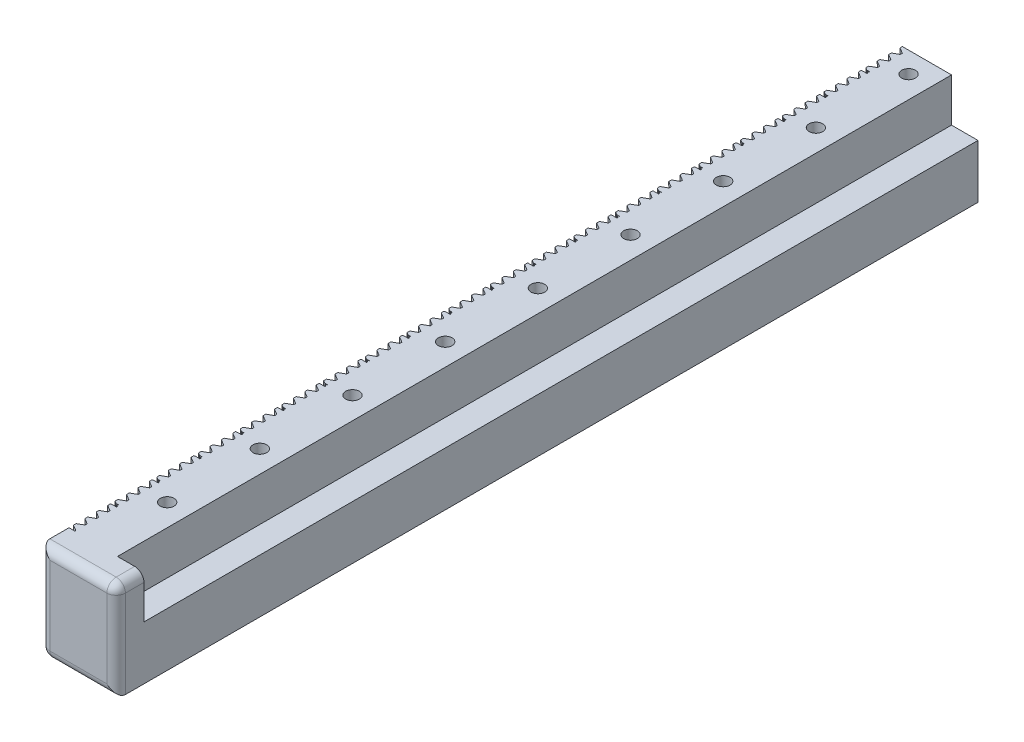
SolidWorks part; units mm, degrees
ref_plane "Front Plane" through (0, 0, 0) normal (0, 0, 1) x (1, 0, 0)
ref_plane "Top Plane" through (0, 0, 0) normal (0, 1, 0) x (1, 0, 0)
ref_plane "Right Plane" through (0, 0, 0) normal (1, 0, 0) x (0, 0, -1)
sketch "Sketch1" plane through (0, 0, 0) normal (0, 0, 1) x (1, 0, 0)
  line L0 (8.155, 3.5595) -> (8.155, -2.2289)
  line L1 (6.255, 0) -> (0.2882, 0)
  line L3 (0, 8.253) -> (5.3, 8.253)
  line L4 (5.3, 3.5595) -> (5.3, 8.253)
  line L5 (0.2882, 0) -> (0, 8.253)
  line L7 (5.3, 3.5595) -> (8.155, 3.5595)
  line L11 (8.155, -2.2289) -> (6.255, -2.2289)
  line L12 (6.255, 0) -> (6.255, -2.2289)
  dimension "D1" = 5.3
  dimension "D2" = 8.253
  dimension "D3" = 1.9
  dimension "D4" = 2.855
  dimension "D6" = 88
extrude "Boss-Extrude1" add sketch "Sketch1" along normal blind 90
sketch "Sketch2" plane through (0, 0, 90) normal (0, 0, 1) x (1, 0, 0)
  line L1 (0, 8.253) -> (8.155, 8.253)
  line L2 (0, 8.253) -> (0, -2.2289)
  line L3 (0, -2.2289) -> (8.155, -2.2289)
  line L4 (8.155, 8.253) -> (8.155, -2.2289)
extrude "Boss-Extrude2" add sketch "Sketch2" along normal blind 3
fillet "Fillet1" radius 1 6 edges at (4.0775, 8.253, 93) (8.155, 3.0121, 93) (4.0775, -2.2289, 93) (0, 3.0121, 93) (0, -2.2289, 91.5) (8.155, 8.253, 91.5)
sketch "Sketch3" plane through (5.3, 0, 0) normal (0, 1, 0) x (0, 0, -1)
  line L0 (-87.5812, 4.6774) -> (-88.0715, 5.5507)
  line L1 (-88.0715, 5.5507) -> (-88.5898, 4.6774)
  line L2 (-88.8112, 4.6774) -> (-89.3015, 5.5507)
  line L3 (-89.3015, 5.5507) -> (-89.8198, 4.6774)
  line L4 (-89.3983, 4.4813) -> (-88.7803, 4.4739) [skipped]
  line L5 (-86.3512, 4.6774) -> (-86.8415, 5.5507)
  line L6 (-86.8415, 5.5507) -> (-87.3598, 4.6774)
  line L7 (-85.1212, 4.6774) -> (-85.6115, 5.5507)
  line L8 (-85.6115, 5.5507) -> (-86.1298, 4.6774)
  line L149 (-89.9324, 4.6774) -> (-89.9324, 6.9221)
  line L150 (-89.9324, 6.9221) -> (-85.1212, 6.9221)
  line L154 (-89.8198, 4.6774) -> (-89.9324, 4.6774)
  line L155 (-88.5898, 4.6774) -> (-88.8112, 4.6774)
  line L156 (-87.3598, 4.6774) -> (-87.5812, 4.6774)
  line L157 (-86.1298, 4.6774) -> (-86.3512, 4.6774)
  line L158 (-85.1212, 6.9221) -> (-85.1212, 4.6774)
  line L160 (-83.1621, 7.6054) -> (-83.4775, 7.0739) [skipped]
  line L161 (-83.735, 6.5902) -> (-84.3402, 7.668) [skipped]
  line L162 (-81.9321, 7.6054) -> (-82.5629, 6.5424) [skipped]
  line L163 (-82.505, 6.5902) -> (-83.1102, 7.668) [skipped]
  line L164 (-80.7021, 7.6054) -> (-81.3329, 6.5424) [skipped]
  line L165 (-81.275, 6.5902) -> (-81.8802, 7.668) [skipped]
  line L166 (-79.4721, 7.6054) -> (-80.1029, 6.5424) [skipped]
  line L167 (-80.045, 6.5902) -> (-80.6502, 7.668) [skipped]
  line L168 (-78.2421, 7.6054) -> (-78.8729, 6.5424) [skipped]
  line L169 (-78.815, 6.5902) -> (-79.4202, 7.668) [skipped]
  line L170 (-77.0121, 7.6054) -> (-77.6429, 6.5424) [skipped]
  line L171 (-75.7821, 7.6054) -> (-76.4129, 6.5424) [skipped]
  line L172 (-84.965, 6.5902) -> (-85.5702, 7.668) [skipped]
  line L173 (-49.295, 6.5902) -> (-49.9002, 7.668) [skipped]
  line L174 (-47.4921, 7.6054) -> (-48.1229, 6.5424) [skipped]
  line L175 (-48.065, 6.5902) -> (-48.6702, 7.668) [skipped]
  line L176 (-46.2621, 7.6054) -> (-46.8929, 6.5424) [skipped]
  line L177 (-46.835, 6.5902) -> (-47.4402, 7.668) [skipped]
  line L178 (-45.0321, 7.6054) -> (-45.6629, 6.5424) [skipped]
  line L179 (-45.605, 6.5902) -> (-46.2102, 7.668) [skipped]
  line L180 (-43.8021, 7.6054) -> (-44.4329, 6.5424) [skipped]
  line L181 (-44.375, 6.5902) -> (-44.9802, 7.668) [skipped]
  line L182 (-42.5721, 7.6054) -> (-43.2029, 6.5424) [skipped]
  line L183 (-43.145, 6.5902) -> (-43.7502, 7.668) [skipped]
  line L184 (-41.3421, 7.6054) -> (-41.9729, 6.5424) [skipped]
  line L185 (-41.915, 6.5902) -> (-42.5202, 7.668) [skipped]
  line L186 (-40.1121, 7.6054) -> (-40.7429, 6.5424) [skipped]
  line L187 (-40.685, 6.5902) -> (-41.2902, 7.668) [skipped]
  line L188 (-38.8821, 7.6054) -> (-39.5129, 6.5424) [skipped]
  line L189 (-37.6521, 7.6054) -> (-38.2829, 6.5424) [skipped]
  line L190 (-38.225, 6.5902) -> (-38.8302, 7.668) [skipped]
  line L191 (-36.4221, 7.6054) -> (-37.0529, 6.5424) [skipped]
  line L192 (-36.995, 6.5902) -> (-37.6002, 7.668) [skipped]
  line L193 (-35.1921, 7.6054) -> (-35.8229, 6.5424) [skipped]
  line L194 (-35.765, 6.5902) -> (-36.3702, 7.668) [skipped]
  line L195 (-33.9621, 7.6054) -> (-34.5929, 6.5424) [skipped]
  line L196 (-34.535, 6.5902) -> (-35.1402, 7.668) [skipped]
  line L197 (-32.7321, 7.6054) -> (-33.3629, 6.5424) [skipped]
  line L198 (-33.305, 6.5902) -> (-33.9102, 7.668) [skipped]
  line L199 (-31.5021, 7.6054) -> (-32.1329, 6.5424) [skipped]
  line L200 (-32.075, 6.5902) -> (-32.6802, 7.668) [skipped]
  line L201 (-30.2721, 7.6054) -> (-30.9029, 6.5424) [skipped]
  line L202 (-30.845, 6.5902) -> (-31.4502, 7.668) [skipped]
  line L203 (-29.0421, 7.6054) -> (-29.6729, 6.5424) [skipped]
  line L204 (-29.615, 6.5902) -> (-30.2202, 7.668) [skipped]
  line L205 (-27.8121, 7.6054) -> (-28.4429, 6.5424) [skipped]
  line L206 (-28.385, 6.5902) -> (-28.9902, 7.668) [skipped]
  line L207 (-26.5821, 7.6054) -> (-27.2129, 6.5424) [skipped]
  line L208 (-27.155, 6.5902) -> (-27.7602, 7.668) [skipped]
  line L209 (-25.3521, 7.6054) -> (-25.9829, 6.5424) [skipped]
  line L210 (-25.925, 6.5902) -> (-26.5302, 7.668) [skipped]
  line L211 (-24.1221, 7.6054) -> (-24.7529, 6.5424) [skipped]
  line L212 (-24.695, 6.5902) -> (-25.3002, 7.668) [skipped]
  line L213 (-22.8921, 7.6054) -> (-23.5229, 6.5424) [skipped]
  line L214 (-23.465, 6.5902) -> (-24.0702, 7.668) [skipped]
  line L215 (-21.6621, 7.6054) -> (-22.2929, 6.5424) [skipped]
  line L216 (-22.235, 6.5902) -> (-22.8402, 7.668) [skipped]
  line L217 (-20.4321, 7.6054) -> (-21.0629, 6.5424) [skipped]
  line L218 (-21.005, 6.5902) -> (-21.6102, 7.668) [skipped]
  line L219 (-19.2021, 7.6054) -> (-19.8329, 6.5424) [skipped]
  line L220 (-19.775, 6.5902) -> (-20.3802, 7.668) [skipped]
  line L221 (-17.9721, 7.6054) -> (-18.6029, 6.5424) [skipped]
  line L222 (-18.545, 6.5902) -> (-19.1502, 7.668) [skipped]
  line L223 (-16.7421, 7.6054) -> (-17.3729, 6.5424) [skipped]
  line L224 (-17.315, 6.5902) -> (-17.9202, 7.668) [skipped]
  line L225 (-15.5121, 7.6054) -> (-16.1429, 6.5424) [skipped]
  line L226 (-16.085, 6.5902) -> (-16.6902, 7.668) [skipped]
  line L227 (-14.2821, 7.6054) -> (-14.9129, 6.5424) [skipped]
  line L228 (-14.855, 6.5902) -> (-15.4602, 7.668) [skipped]
  line L229 (-13.0521, 7.6054) -> (-13.6829, 6.5424) [skipped]
  line L230 (-13.625, 6.5902) -> (-14.2302, 7.668) [skipped]
  line L231 (-11.8221, 7.6054) -> (-12.4529, 6.5424) [skipped]
  line L232 (-12.395, 6.5902) -> (-13.0002, 7.668) [skipped]
  line L233 (-10.5921, 7.6054) -> (-11.2229, 6.5424) [skipped]
  line L234 (-11.165, 6.5902) -> (-11.7702, 7.668) [skipped]
  line L235 (-9.3621, 7.6054) -> (-9.9929, 6.5424) [skipped]
  line L236 (-9.935, 6.5902) -> (-10.5402, 7.668) [skipped]
  line L237 (-8.1321, 7.6054) -> (-8.7629, 6.5424) [skipped]
  line L238 (-8.705, 6.5902) -> (-9.3102, 7.668) [skipped]
  line L239 (-6.9021, 7.6054) -> (-7.5329, 6.5424) [skipped]
  line L240 (-7.475, 6.5902) -> (-8.0802, 7.668) [skipped]
  line L241 (-5.6721, 7.6054) -> (-6.3029, 6.5424) [skipped]
  line L242 (-6.245, 6.5902) -> (-6.8502, 7.668) [skipped]
  line L243 (-4.4421, 7.6054) -> (-5.0729, 6.5424) [skipped]
  line L244 (-5.015, 6.5902) -> (-5.6202, 7.668) [skipped]
  line L245 (-3.2121, 7.6054) -> (-3.8429, 6.5424) [skipped]
  line L246 (-3.785, 6.5902) -> (-4.3902, 7.668) [skipped]
  line L247 (-1.9821, 7.6054) -> (-2.6129, 6.5424) [skipped]
  line L248 (-2.555, 6.5902) -> (-3.1602, 7.668) [skipped]
  line L249 (-0.7521, 7.6054) -> (-1.3829, 6.5424) [skipped]
  line L250 (-1.325, 6.5902) -> (-1.9302, 7.668) [skipped]
  line L251 (0.4779, 7.6054) -> (-0.1529, 6.5424) [skipped]
  line L252 (-0.095, 6.5902) -> (-0.7002, 7.668) [skipped]
  line L253 (1.7079, 7.6054) -> (1.0771, 6.5424) [skipped]
  line L254 (-39.455, 6.5902) -> (-40.0602, 7.668) [skipped]
  line L255 (-76.355, 6.5902) -> (-76.9602, 7.668) [skipped]
  line L256 (-74.5521, 7.6054) -> (-75.1829, 6.5424) [skipped]
  line L257 (-75.125, 6.5902) -> (-75.7302, 7.668) [skipped]
  line L258 (-73.3221, 7.6054) -> (-73.9529, 6.5424) [skipped]
  line L259 (-73.895, 6.5902) -> (-74.5002, 7.668) [skipped]
  line L260 (-72.0921, 7.6054) -> (-72.7229, 6.5424) [skipped]
  line L261 (-72.665, 6.5902) -> (-73.2702, 7.668) [skipped]
  line L262 (-70.8621, 7.6054) -> (-71.4929, 6.5424) [skipped]
  line L263 (-71.435, 6.5902) -> (-72.0402, 7.668) [skipped]
  line L264 (-69.6321, 7.6054) -> (-70.2629, 6.5424) [skipped]
  line L265 (-70.205, 6.5902) -> (-70.8102, 7.668) [skipped]
  line L266 (-68.4021, 7.6054) -> (-69.0329, 6.5424) [skipped]
  line L267 (-68.975, 6.5902) -> (-69.5802, 7.668) [skipped]
  line L268 (-67.1721, 7.6054) -> (-67.8029, 6.5424) [skipped]
  line L269 (-67.745, 6.5902) -> (-68.3502, 7.668) [skipped]
  line L270 (-65.9421, 7.6054) -> (-66.5729, 6.5424) [skipped]
  line L271 (-66.515, 6.5902) -> (-67.1202, 7.668) [skipped]
  line L272 (-64.7121, 7.6054) -> (-65.3429, 6.5424) [skipped]
  line L273 (-65.285, 6.5902) -> (-65.8902, 7.668) [skipped]
  line L274 (-63.4821, 7.6054) -> (-64.1129, 6.5424) [skipped]
  line L275 (-64.055, 6.5902) -> (-64.6602, 7.668) [skipped]
  line L276 (-62.2521, 7.6054) -> (-62.8829, 6.5424) [skipped]
  line L277 (-62.825, 6.5902) -> (-63.4302, 7.668) [skipped]
  line L278 (-61.0221, 7.6054) -> (-61.6529, 6.5424) [skipped]
  line L279 (-61.595, 6.5902) -> (-62.2002, 7.668) [skipped]
  line L280 (-59.7921, 7.6054) -> (-60.4229, 6.5424) [skipped]
  line L281 (-60.365, 6.5902) -> (-60.9702, 7.668) [skipped]
  line L282 (-58.5621, 7.6054) -> (-59.1929, 6.5424) [skipped]
  line L283 (-59.135, 6.5902) -> (-59.7402, 7.668) [skipped]
  line L284 (-57.3321, 7.6054) -> (-57.9629, 6.5424) [skipped]
  line L285 (-57.905, 6.5902) -> (-58.5102, 7.668) [skipped]
  line L286 (-56.1021, 7.6054) -> (-56.7329, 6.5424) [skipped]
  line L287 (-56.675, 6.5902) -> (-57.2802, 7.668) [skipped]
  line L288 (-54.8721, 7.6054) -> (-55.5029, 6.5424) [skipped]
  line L289 (-55.445, 6.5902) -> (-56.0502, 7.668) [skipped]
  line L290 (-53.6421, 7.6054) -> (-54.2729, 6.5424) [skipped]
  line L291 (-54.215, 6.5902) -> (-54.8202, 7.668) [skipped]
  line L292 (-52.4121, 7.6054) -> (-53.0429, 6.5424) [skipped]
  line L293 (-52.985, 6.5902) -> (-53.5902, 7.668) [skipped]
  line L294 (-51.1821, 7.6054) -> (-51.8129, 6.5424) [skipped]
  line L295 (-51.755, 6.5902) -> (-52.3602, 7.668) [skipped]
  line L296 (-49.9521, 7.6054) -> (-50.5829, 6.5424) [skipped]
  line L297 (-50.525, 6.5902) -> (-51.1302, 7.668) [skipped]
  line L298 (-48.7221, 7.6054) -> (-49.3529, 6.5424) [skipped]
  line L299 (-77.585, 6.5902) -> (-78.1902, 7.668) [skipped]
  circle A0 centre (-89.3101, 4.8371) radius 0.3568 construction
  arc A1 (-87.7689, 5.0118) -> (-88.3869, 5.0193) centre (-88.0801, 4.8371) ccw construction
  arc A2 (-86.5389, 5.0118) -> (-87.1692, 4.6774) centre (-86.8501, 4.8371) ccw construction
  arc A3 (-85.9392, 4.6774) -> (-85.301, 4.6774) centre (-85.6201, 4.8371) ccw construction
  arc A74 (-85.3089, 5.0118) -> (-85.9269, 5.0193) centre (-85.6201, 4.8371) ccw construction
  arc A75 (-84.7112, 4.6816) -> (-84.7116, 4.6824) centre (-84.3901, 4.8371) ccw construction
  circle A76 centre (-83.1601, 4.8371) radius 0.3568 construction
  circle A77 centre (-81.9301, 4.8371) radius 0.3568 construction
  circle A78 centre (-80.7001, 4.8371) radius 0.3568 construction
  circle A79 centre (-79.4701, 4.8371) radius 0.3568 construction
  circle A80 centre (-78.2401, 4.8371) radius 0.3568 construction
  circle A81 centre (-77.0101, 4.8371) radius 0.3568 construction
  circle A82 centre (-48.7201, 4.8371) radius 0.3568 construction
  circle A83 centre (-47.4901, 4.8371) radius 0.3568 construction
  circle A84 centre (-46.2601, 4.8371) radius 0.3568 construction
  circle A85 centre (-45.0301, 4.8371) radius 0.3568 construction
  circle A86 centre (-43.8001, 4.8371) radius 0.3568 construction
  circle A87 centre (-42.5701, 4.8371) radius 0.3568 construction
  circle A88 centre (-41.3401, 4.8371) radius 0.3568 construction
  circle A89 centre (-40.1101, 4.8371) radius 0.3568 construction
  circle A90 centre (-38.8801, 4.8371) radius 0.3568 construction
  circle A91 centre (-37.6501, 4.8371) radius 0.3568 construction
  circle A92 centre (-36.4201, 4.8371) radius 0.3568 construction
  circle A93 centre (-35.1901, 4.8371) radius 0.3568 construction
  circle A94 centre (-33.9601, 4.8371) radius 0.3568 construction
  circle A95 centre (-32.7301, 4.8371) radius 0.3568 construction
  circle A96 centre (-31.5001, 4.8371) radius 0.3568 construction
  circle A97 centre (-30.2701, 4.8371) radius 0.3568 construction
  circle A98 centre (-29.0401, 4.8371) radius 0.3568 construction
  circle A99 centre (-27.8101, 4.8371) radius 0.3568 construction
  circle A100 centre (-26.5801, 4.8371) radius 0.3568 construction
  circle A101 centre (-25.3501, 4.8371) radius 0.3568 construction
  circle A102 centre (-24.1201, 4.8371) radius 0.3568 construction
  circle A103 centre (-22.8901, 4.8371) radius 0.3568 construction
  circle A104 centre (-21.6601, 4.8371) radius 0.3568 construction
  circle A105 centre (-20.4301, 4.8371) radius 0.3568 construction
  circle A106 centre (-19.2001, 4.8371) radius 0.3568 construction
  circle A107 centre (-17.9701, 4.8371) radius 0.3568 construction
  circle A108 centre (-16.7401, 4.8371) radius 0.3568 construction
  circle A109 centre (-15.5101, 4.8371) radius 0.3568 construction
  circle A110 centre (-14.2801, 4.8371) radius 0.3568 construction
  circle A111 centre (-13.0501, 4.8371) radius 0.3568 construction
  circle A112 centre (-11.8201, 4.8371) radius 0.3568 construction
  circle A113 centre (-10.5901, 4.8371) radius 0.3568 construction
  circle A114 centre (-9.3601, 4.8371) radius 0.3568 construction
  circle A115 centre (-8.1301, 4.8371) radius 0.3568 construction
  circle A116 centre (-6.9001, 4.8371) radius 0.3568 construction
  circle A117 centre (-5.6701, 4.8371) radius 0.3568 construction
  circle A118 centre (-4.4401, 4.8371) radius 0.3568 construction
  circle A119 centre (-3.2101, 4.8371) radius 0.3568 construction
  circle A120 centre (-1.9801, 4.8371) radius 0.3568 construction
  circle A121 centre (-0.7501, 4.8371) radius 0.3568 construction
  circle A122 centre (0.4799, 4.8371) radius 0.3568 construction
  circle A123 centre (-75.7801, 4.8371) radius 0.3568 construction
  circle A124 centre (-74.5501, 4.8371) radius 0.3568 construction
  circle A125 centre (-73.3201, 4.8371) radius 0.3568 construction
  circle A126 centre (-72.0901, 4.8371) radius 0.3568 construction
  circle A127 centre (-70.8601, 4.8371) radius 0.3568 construction
  circle A128 centre (-69.6301, 4.8371) radius 0.3568 construction
  circle A129 centre (-68.4001, 4.8371) radius 0.3568 construction
  circle A130 centre (-67.1701, 4.8371) radius 0.3568 construction
  circle A131 centre (-65.9401, 4.8371) radius 0.3568 construction
  circle A132 centre (-64.7101, 4.8371) radius 0.3568 construction
  circle A133 centre (-63.4801, 4.8371) radius 0.3568 construction
  circle A134 centre (-62.2501, 4.8371) radius 0.3568 construction
  circle A135 centre (-61.0201, 4.8371) radius 0.3568 construction
  circle A136 centre (-59.7901, 4.8371) radius 0.3568 construction
  circle A137 centre (-58.5601, 4.8371) radius 0.3568 construction
  circle A138 centre (-57.3301, 4.8371) radius 0.3568 construction
  circle A139 centre (-56.1001, 4.8371) radius 0.3568 construction
  circle A140 centre (-54.8701, 4.8371) radius 0.3568 construction
  circle A141 centre (-53.6401, 4.8371) radius 0.3568 construction
  circle A142 centre (-52.4101, 4.8371) radius 0.3568 construction
  circle A143 centre (-51.1801, 4.8371) radius 0.3568 construction
  circle A144 centre (-49.9501, 4.8371) radius 0.3568 construction
  point P1 (0, 0)
  dimension "D2" = 74
extrude "Cut-Extrude2" cut sketch "Sketch3" along normal blind 13
pattern_linear "LPattern1" count 20 spacing 4.5 along (0, 0, -1) of "Cut-Extrude2"
sketch "Sketch4" plane through (0, 8.253, 0) normal (0, 1, 0) x (1, 0, 0)
  circle A0 centre (2.9148, -2.2514) radius 0.7382
  circle A1 centre (2.9148, -12.2514) radius 0.7382
  circle A2 centre (2.9148, -22.2514) radius 0.7382
  circle A3 centre (2.9148, -32.2514) radius 0.7382
  circle A4 centre (2.9148, -42.2514) radius 0.7382
  circle A5 centre (2.9148, -52.2514) radius 0.7382
  circle A6 centre (2.9148, -62.2514) radius 0.7382
  circle A7 centre (2.9148, -72.2514) radius 0.7382
  circle A8 centre (2.9148, -82.2514) radius 0.7382
  dimension "D1" = 9
extrude "Cut-Extrude3" cut sketch "Sketch4" against normal blind 18
